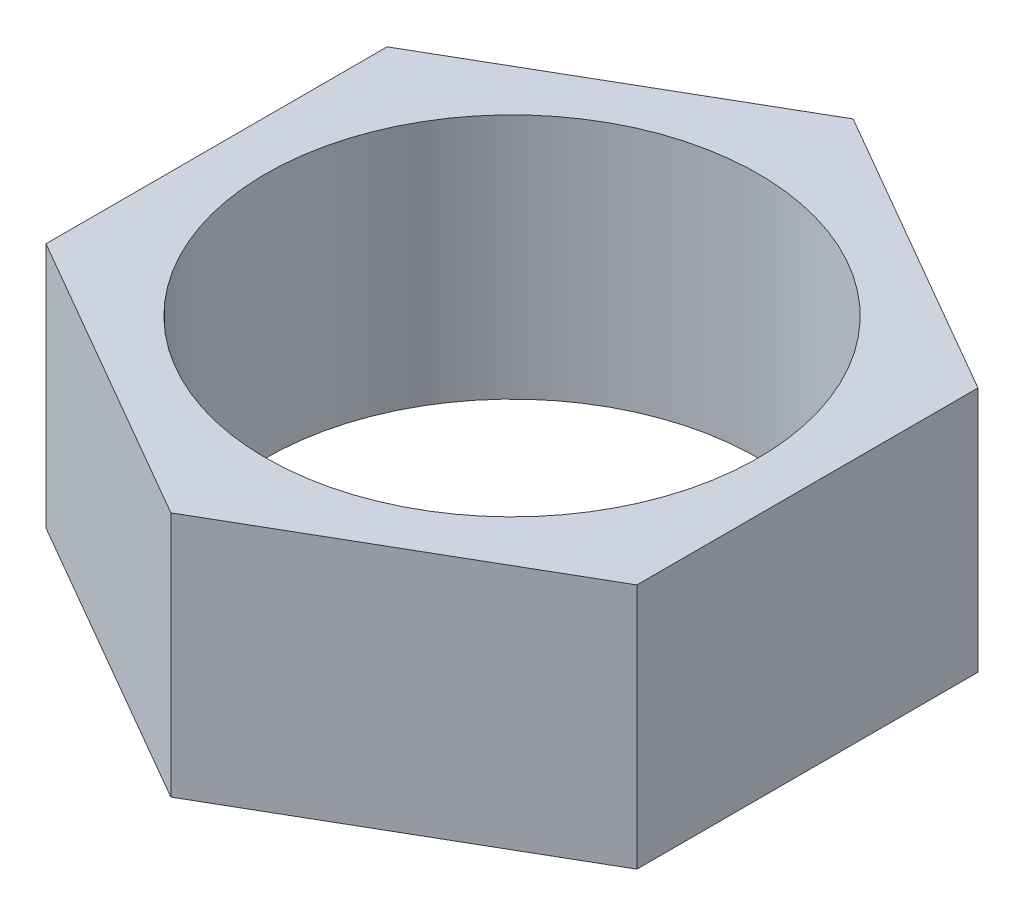
SolidWorks part; units mm, degrees
ref_plane "Front Plane" through (0, 0, 0) normal (0, 0, 1) x (1, 0, 0)
ref_plane "Top Plane" through (0, 0, 0) normal (0, 1, 0) x (1, 0, 0)
ref_plane "Right Plane" through (0, 0, 0) normal (1, 0, 0) x (0, 0, -1)
sketch "Sketch1" plane through (0, 0, 0) normal (0, 1, 0) x (1, 0, 0)
  line L1 (-0.3, 0.1732) -> (-0.3, -0.1732)
  line L2 (-0.3, -0.1732) -> (0, -0.3464)
  line L3 (0, -0.3464) -> (0.3, -0.1732)
  line L4 (0.3, -0.1732) -> (0.3, 0.1732)
  line L5 (0.3, 0.1732) -> (0, 0.3464)
  line L6 (0, 0.3464) -> (-0.3, 0.1732)
  circle A0 centre (0, 0) radius 0.3 construction
  dimension "D1" = 0.6
extrude "Boss-Extrude1" add sketch "Sketch1" along normal blind 0.25
sketch "Sketch2" plane through (0, 0.25, 0) normal (0, 1, 0) x (1, 0, 0)
  circle A0 centre (0, 0) radius 0.25
  point P2 (0, 0)
  dimension "D1" = 0.5
extrude "Cut-Extrude1" cut sketch "Sketch2" against normal blind 0.25
